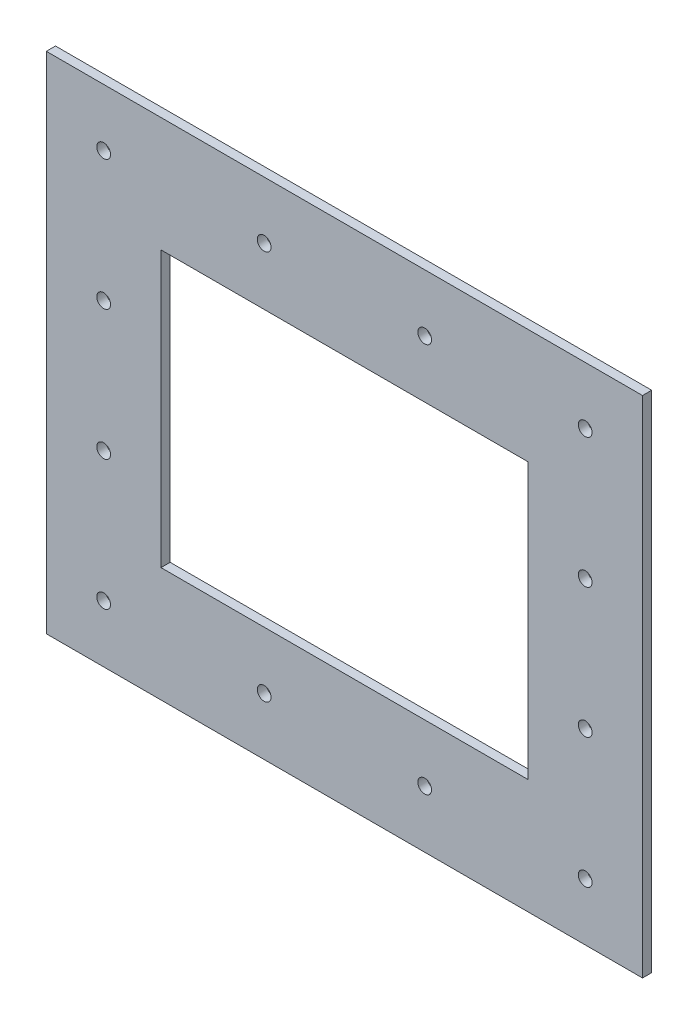
SolidWorks part; units mm, degrees
ref_plane "Alzado" through (0, 0, 0) normal (0, 0, 1) x (1, 0, 0)
ref_plane "Planta" through (0, 0, 0) normal (0, 1, 0) x (1, 0, 0)
ref_plane "Vista lateral" through (0, 0, 0) normal (1, 0, 0) x (0, 0, -1)
sketch "Croquis1" plane through (0, 0, 0) normal (0, 0, 1) x (1, 0, 0)
  line L0 (25, 25) -> (25, 85)
  line L1 (0, 0) -> (130, 0)
  line L2 (0, 0) -> (0, 110)
  line L3 (0, 110) -> (130, 110)
  line L4 (130, 0) -> (130, 110)
  line L5 (25, 85) -> (105, 85)
  line L6 (105, 25) -> (105, 85)
  line L7 (25, 25) -> (105, 25)
  dimension "D1" = 130
  dimension "D2" = 110
  dimension "D3" = 25
extrude "Saliente-Extruir1" add sketch "Croquis1" along normal blind 2
sketch "Croquis2" plane through (0, 0, 0) normal (0, 0, 1) x (1, 0, 0)
  line L0 (130, 110) -> (0, 110) construction
  line L1 (105, 85) -> (25, 85) construction
  line L2 (130, 110) -> (0, 110) construction
  line L3 (105, 85) -> (25, 85) construction
  line L4 (0, 97.5) -> (130, 97.5) construction
  line L5 (0, 110) -> (0, 0) construction
  line L6 (130, 0) -> (130, 110) construction
  line L7 (65, 85) -> (65, 25) construction
  line L8 (25, 25) -> (105, 25) construction
  line L9 (25, 55) -> (105, 55) construction
  line L10 (25, 85) -> (25, 25) construction
  line L11 (105, 25) -> (105, 85) construction
  circle A0 centre (12.5, 97.5) radius 1.5
  circle A26 centre (47.5, 97.5) radius 1.5
  circle A27 centre (82.5, 97.5) radius 1.5
  circle A28 centre (117.5, 97.5) radius 1.5
  circle A29 centre (12.5, 69.17) radius 1.5
  circle A30 centre (12.5, 40.84) radius 1.5
  circle A31 centre (117.5, 12.5) radius 1.5
  circle A32 centre (82.5, 12.5) radius 1.5
  circle A33 centre (47.5, 12.5) radius 1.5
  circle A34 centre (12.5, 12.5) radius 1.5
  circle A35 centre (117.5, 40.84) radius 1.5
  circle A36 centre (117.5, 69.17) radius 1.5
  point P14 (128.75, 97.5)
  point P15 (1.25, 1.15)
  dimension "D4" = 1.15
  dimension "D5" = 4
  dimension "D6" = 3
  dimension "D7" = 3
  dimension "D1" = 12.5
  dimension "D2" = 12.5
  dimension "D3" = 1.25
extrude "Cortar-Extruir2" cut sketch "Croquis2" along normal through all
